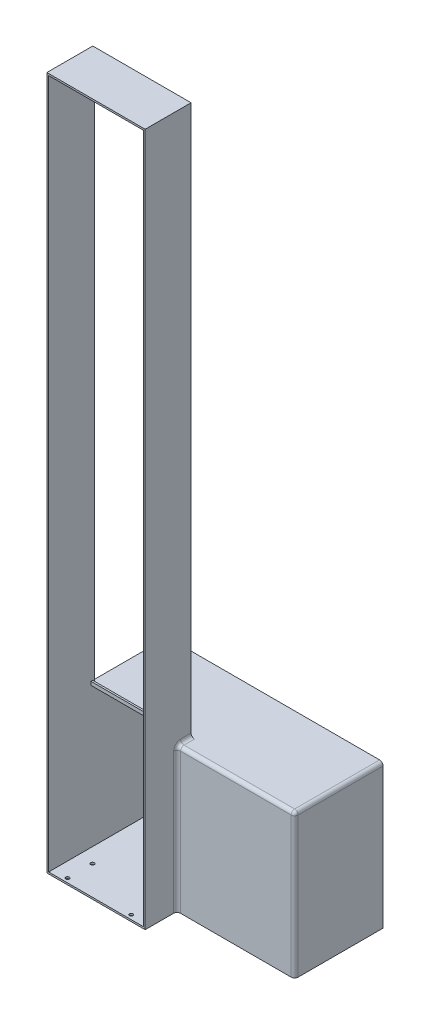
SolidWorks part; units mm, degrees
material "AISI 4340 Steel, annealed"
ref_plane "Front Plane" through (0, 0, 0) normal (0, 0, 1) x (1, 0, 0)
ref_plane "Top Plane" through (0, 0, 0) normal (0, 1, 0) x (1, 0, 0)
ref_plane "Right Plane" through (0, 0, 0) normal (1, 0, 0) x (0, 0, -1)
sketch "Pulley link" plane through (0, 0, 0) normal (0, 0, 1) x (1, 0, 0)
  line L0 (0, 850) -> (0, -850) construction
  line L1 (105, 850) -> (105, -850)
  line L2 (-105, 850) -> (-105, -850)
  arc A0 (105, 850) -> (-105, 850) centre (0, 850) ccw
  arc A1 (-105, -850) -> (105, -850) centre (0, -850) ccw
  point P3 (0, 0)
  dimension "D2" = 105
  dimension "D1" = 1700
sketch "Sketch3" plane through (0, -985.6187, 0) normal (0, -1, 0) x (1, 0, 0)
  line L0 (-140, 90.3875) -> (140, 90.3875)
  line L1 (140, 90.3875) -> (140, -0.5375)
  line L2 (140, -0.5375) -> (474.951, -0.5375)
  line L3 (474.951, -0.5375) -> (474.951, -252.6145)
  line L4 (474.951, -252.6145) -> (-140, -252.6145)
  line L5 (-140, -252.6145) -> (-140, 90.3875)
  line L6 (-120, 34.4098) -> (-120, 15.5898) construction
  line L7 (108, 90.3875) -> (-113, 90.3875) construction
  line L8 (120, 34.4098) -> (120, 15.5898) construction
  line L9 (393.3, -10.5375) -> (193.3, -10.5375) construction
  line L10 (464.951, -178.2255) -> (464.951, -20.9995) construction
  line L11 (400.943, -242.6145) -> (337.443, -242.6145) construction
  circle A0 centre (88, -194.6125) radius 5 construction
  circle A1 centre (-93, -194.6125) radius 5 construction
  circle A2 centre (88, 7.3875) radius 5 construction
  circle A3 centre (-93, 7.3875) radius 5 construction
  circle A4 centre (-93, 78.3875) radius 5 construction
  circle A5 centre (88, 78.3875) radius 5 construction
  circle A6 centre (88, -194.6125) radius 5
  circle A7 centre (-93, -194.6125) radius 5
  circle A8 centre (88, 7.3875) radius 5
  circle A9 centre (-93, 7.3875) radius 5
  circle A10 centre (-93, 78.3875) radius 5
  circle A11 centre (88, 78.3875) radius 5
  dimension "D1" = 20
  dimension "D2" = 20
  dimension "D3" = 10
  dimension "D4" = 10
  dimension "D5" = 10
extrude "Bottom plate" add sketch "Sketch3" along normal blind 5
sketch "Sketch4" plane through (0, -985.6187, 0) normal (0, 1, 0) x (1, 0, 0)
  line L6 (-135, 252.6145) -> (-135, -90.3875)
  line L7 (135, -90.3875) -> (135, 5.5375)
  line L8 (135, 5.5375) -> (469.951, 5.5375)
  line L9 (469.951, 5.5375) -> (469.951, 252.6145)
  line L10 (-135, 252.6145) -> (-140, 252.6145)
  line L11 (135, -90.3875) -> (140, -90.3875)
  line L18 (-140, 252.6145) -> (-140, -90.3875)
  line L19 (-140, -90.3875) -> (140, -90.3875)
  line L20 (140, -90.3875) -> (140, 0.5375)
  line L21 (140, 0.5375) -> (474.951, 0.5375)
  line L22 (474.951, 0.5375) -> (474.951, 252.6145)
  line L23 (474.951, 252.6145) -> (-140, 252.6145)
  line L24 (-140, 252.6145) -> (-140, -90.3875)
  line L25 (-140, -90.3875) -> (-135, -90.3875)
  line L26 (140, -90.3875) -> (140, 0.5375)
  line L27 (140, 0.5375) -> (474.951, 0.5375)
  line L28 (474.951, 0.5375) -> (474.951, 252.6145)
  line L29 (474.951, 252.6145) -> (469.951, 252.6145)
  dimension "D2" = 5
  dimension "D3" = 5
  dimension "D4" = 5
  dimension "D5" = 5
  dimension "D1" = 0
extrude "Vertical walls" add sketch "Sketch4" along normal blind 400
sketch "Sketch6" plane through (0, -585.6187, 0) normal (0, 1, 0) x (1, 0, 0)
  line L0 (135, -90.3875) -> (135, 35.3945)
  line L1 (-135, 252.6145) -> (469.951, 252.6145) construction
  line L2 (135, 252.6145) -> (474.951, 252.6145)
  line L3 (474.951, 252.6145) -> (474.951, 0.5375)
  line L4 (-140, 252.6145) -> (-140, -90.3875)
  line L5 (-140, -90.3875) -> (-135, -90.3875)
  line L6 (-135, -90.3875) -> (-135, 252.6145)
  line L7 (-135, 252.6145) -> (-140, 252.6145)
  line L8 (-140, 252.6145) -> (-140, -90.3875)
  line L9 (-140, -90.3875) -> (-135, -90.3875)
  line L10 (-135, -90.3875) -> (-135, 35.3945)
  line L11 (-135, 252.6145) -> (-140, 252.6145)
  line L12 (474.951, 0.5375) -> (140, 0.5375)
  line L13 (140, 0.5375) -> (140, -90.3875)
  line L14 (140, -90.3875) -> (135, -90.3875)
  line L15 (-135, 252.6145) -> (135, 252.6145)
  line L16 (135, 35.3945) -> (-135, 35.3945)
  dimension "D2" = 217.22
  dimension "D1" = 0
extrude "Mid horizontal plate" add sketch "Sketch6" along normal blind 5
sketch "Sketch7" plane through (0, -580.6187, 0) normal (0, 1, 0) x (1, 0, 0)
  line L18 (135, -90.3875) -> (135, 40.3945)
  line L19 (135, 40.3945) -> (140, 40.3945)
  line L20 (140, 40.3945) -> (140, -90.3875)
  line L21 (140, -90.3875) -> (135, -90.3875)
  line L22 (140, -90.3875) -> (140, 0.5375) construction
  line L24 (-135, 35.3945) -> (135, 35.3945) construction
  line L26 (-140, -90.3875) -> (-135, -90.3875)
  line L28 (-135, -90.3875) -> (-135, 40.3945)
  line L30 (-135, -90.3875) -> (-135, 252.6145) construction
  line L32 (-135, 40.3945) -> (-140, 40.3945)
  line L34 (-140, 252.6145) -> (-140, -90.3875) construction
  line L35 (-140, 40.3945) -> (-140, -90.3875)
  dimension "D1" = 5
  dimension "D2" = 5
extrude "Rest of vertical extrude" add sketch "Sketch7" along normal blind 1560
sketch "Sketch8" plane through (0, 979.3813, 0) normal (0, 1, 0) x (1, 0, 0)
  line L5 (-140, -90.3875) -> (140, -90.3875)
  line L6 (-140, -90.3875) -> (-140, 40.3945)
  line L7 (-140, 40.3945) -> (140, 40.3945)
  line L8 (140, -90.3875) -> (140, 40.3945)
extrude "Top plate" add sketch "Sketch8" along normal blind 5
fillet "Motor box fillets" radius 10 5 edges at (474.951, -785.6187, -0.5375) (474.951, -580.6187, -126.576) (307.4755, -580.6187, -0.5375) (140, -580.6187, -20.466) (140, -785.6187, -0.5375)
sketch "Sketch10" plane through (135, 0, 0) normal (-1, 0, 0) x (0, 0, 1)
  line L0 (-35.3945, -585.6187) -> (-5.5375, -585.6187) construction
  line L1 (-35.3945, -585.6187) -> (-30.3945, -585.6187)
  line L2 (-35.3945, -585.6187) -> (-35.3945, -575.6187)
  line L3 (-35.3945, -575.6187) -> (-30.3945, -575.6187)
  line L4 (-30.3945, -585.6187) -> (-30.3945, -575.6187)
  dimension "D1" = 10
  dimension "D2" = 5
extrude "Bottom plate lip" add sketch "Sketch10" along normal up to surface (270 mm away) up to face at (-135, -293.1187, -59.504)
